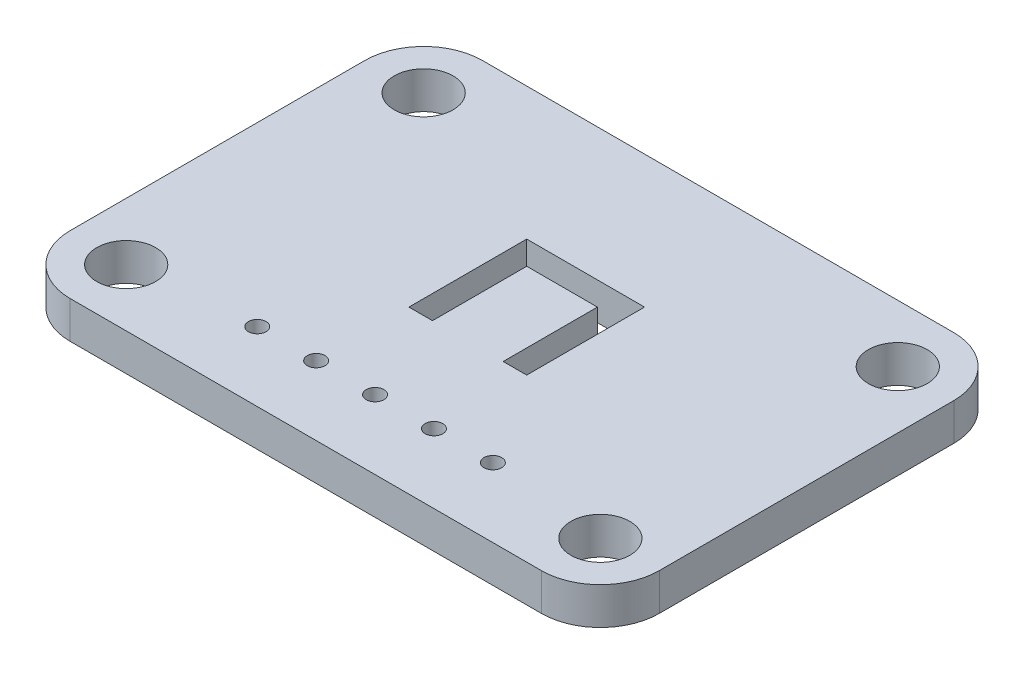
SolidWorks part; units mm, degrees
ref_plane "Front Plane" through (0, 0, 0) normal (0, 0, 1) x (1, 0, 0)
ref_plane "Top Plane" through (0, 0, 0) normal (0, 1, 0) x (1, 0, 0)
ref_plane "Right Plane" through (0, 0, 0) normal (1, 0, 0) x (0, 0, -1)
sketch "Sketch1" plane through (0, 0, 0) normal (0, 1, 0) x (1, 0, 0)
  line L0 (-2.54, -1.905) -> (-1.524, -1.905)
  line L1 (10.16, 8.89) -> (-10.16, 8.89)
  line L2 (12.7, 6.35) -> (12.7, -6.35)
  line L3 (10.16, -8.89) -> (-10.16, -8.89)
  line L4 (-12.7, 6.35) -> (-12.7, -6.35)
  line L5 (12.7, 8.89) -> (-12.7, -8.89) construction
  line L6 (12.7, -8.89) -> (-12.7, 8.89) construction
  line L7 (-1.524, -1.905) -> (-1.524, 2.159)
  line L8 (-1.524, 2.159) -> (1.524, 2.159)
  line L9 (1.524, 2.159) -> (1.524, -1.905)
  line L10 (1.524, -1.905) -> (2.54, -1.905)
  line L11 (2.54, -1.905) -> (2.54, 3.175)
  line L12 (2.54, 3.175) -> (-2.54, 3.175)
  line L13 (-2.54, 3.175) -> (-2.54, -1.905)
  line L14 (0, 0) -> (0, 10.4198) construction
  line L15 (-10.16, 6.35) -> (10.16, -6.35) construction
  line L16 (10.16, 6.35) -> (-10.16, -6.35) construction
  line L17 (0, 0) -> (-8.3012, 0) construction
  arc A0 (10.16, 8.89) -> (12.7, 6.35) centre (10.16, 6.35) cw
  arc A1 (12.7, -6.35) -> (10.16, -8.89) centre (10.16, -6.35) cw
  arc A2 (-10.16, -8.89) -> (-12.7, -6.35) centre (-10.16, -6.35) cw
  arc A3 (-10.16, 8.89) -> (-12.7, 6.35) centre (-10.16, 6.35) ccw
  circle A8 centre (-10.2235, 6.4135) radius 1.27
  circle A9 centre (10.2235, 6.4135) radius 1.27
  circle A10 centre (-10.2235, -6.4135) radius 1.27
  circle A11 centre (10.2235, -6.4135) radius 1.27
  point P0 (0, 0)
  dimension "D1" = 2.54
  dimension "D9" = 2.54
  dimension "D10" = 10.287
  dimension "D11" = 17.907
  dimension "D2" = 17.78
  dimension "D3" = 25.4
  dimension "D4" = 10.16
  dimension "D5" = 5.715
  dimension "D6" = 1.016
  dimension "D7" = 1.016
  dimension "D8" = 6.985
extrude "Boss-Extrude1" add sketch "Sketch1" along normal blind 1.6
sketch "Sketch2" plane through (0, 0, 0) normal (0, -1, 0) x (1, 0, 0)
  line L0 (-10.16, 8.89) -> (10.16, 8.89) construction
  line L1 (-6.604, 7.239) -> (6.604, 7.239)
  line L2 (-6.604, 7.239) -> (-6.604, 4.572)
  line L3 (-6.604, 4.572) -> (6.604, 4.572)
  line L4 (6.604, 7.239) -> (6.604, 4.572)
  line L5 (0, 0) -> (0, 2.4773) construction
  dimension "D1" = 13.208
  dimension "D2" = 2.667
  dimension "D3" = 1.651
extrude "Boss-Extrude2" add sketch "Sketch2" along normal blind 2.159
sketch "Sketch3" plane through (0, -2.159, 0) normal (0, -1, 0) x (1, 0, 0)
  line L0 (-6.604, 5.9055) -> (6.604, 5.9055) construction
  line L1 (-6.604, 7.239) -> (-6.604, 4.572) construction
  line L2 (6.604, 4.572) -> (6.604, 7.239) construction
  line L3 (0, 0) -> (0, 11.811) construction
  circle A0 centre (-5.08, 5.9055) radius 0.381
  circle A1 centre (-2.54, 5.9055) radius 0.381
  circle A2 centre (0, 5.9055) radius 0.381
  circle A3 centre (2.54, 5.9055) radius 0.381
  circle A4 centre (5.08, 5.9055) radius 0.381
  dimension "D2" = 2.54
  dimension "D3" = 0.762
  dimension "D1" = 2.54
extrude "Cut-Extrude1" cut sketch "Sketch3" against normal through all
sketch "Sketch4" plane through (-12.7, 0, 0) normal (-1, 0, 0) x (0, 0, 1)
  line L0 (-6.35, 0) -> (6.35, 0) construction
  line L1 (3.3678, 0) -> (8.4788, 0)
  line L2 (3.3678, 0) -> (3.3678, -3.1476)
  line L3 (3.3678, -3.1476) -> (8.4788, -3.1476)
  line L4 (8.4788, 0) -> (8.4788, -3.1476)
extrude "Cut-Extrude2" cut sketch "Sketch4" against normal through all
sketch "Sketch5" plane through (0, 0, 0) normal (0, -1, 0) x (1, 0, 0)
  text T0 "SHT45"
extrude "Cut-Extrude3" cut sketch "Sketch5" against normal blind 0.0254
